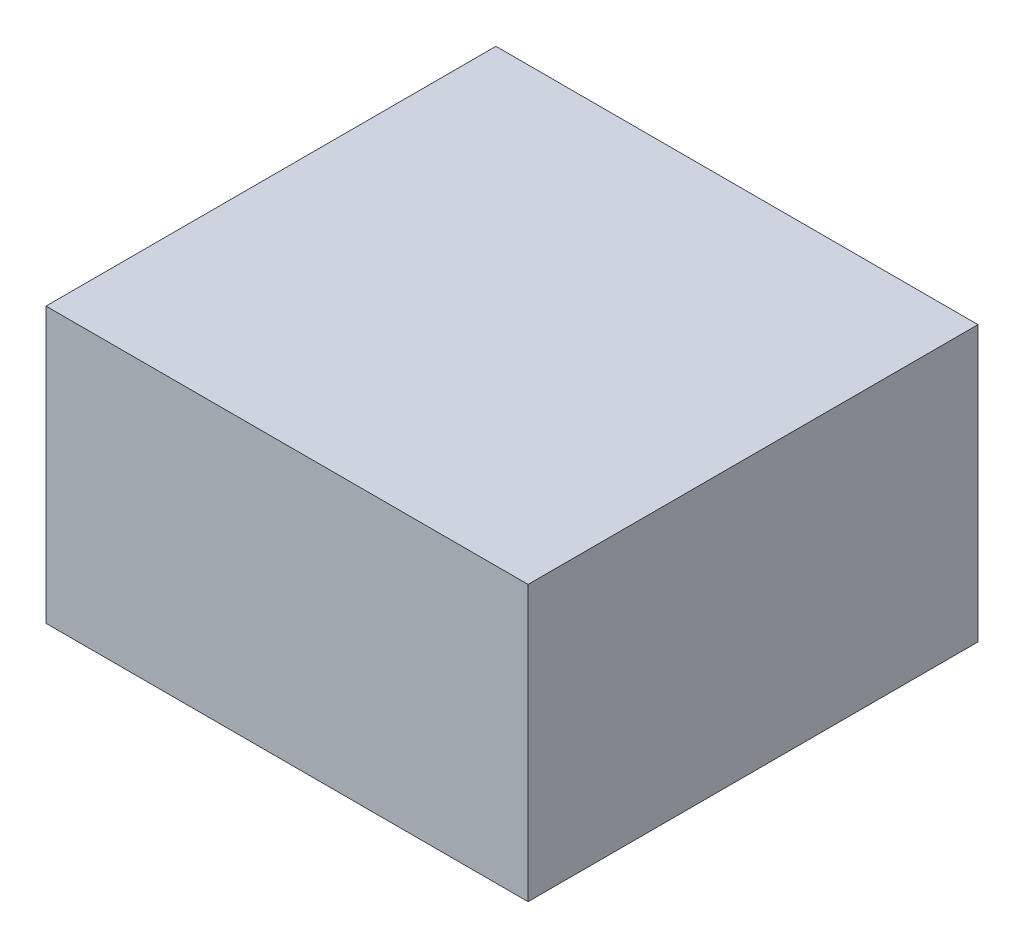
SolidWorks part; units mm, degrees
ref_plane "Front Plane" through (0, 0, 0) normal (0, 0, 1) x (1, 0, 0)
ref_plane "Top Plane" through (0, 0, 0) normal (0, 1, 0) x (1, 0, 0)
ref_plane "Right Plane" through (0, 0, 0) normal (1, 0, 0) x (0, 0, -1)
sketch "Sketch1" plane through (0, 0, 0) normal (0, 1, 0) x (1, 0, 0)
  line L1 (-75, 70) -> (75, 70)
  line L2 (-75, 70) -> (-75, -70)
  line L3 (-75, -70) -> (75, -70)
  line L4 (75, 70) -> (75, -70)
  line L5 (-75, 70) -> (75, -70) construction
  line L6 (-75, -70) -> (75, 70) construction
  point P0 (0, 0)
  dimension "D1" = 140
  dimension "D2" = 150
extrude "Boss-Extrude1" add sketch "Sketch1" along normal blind 85.5
